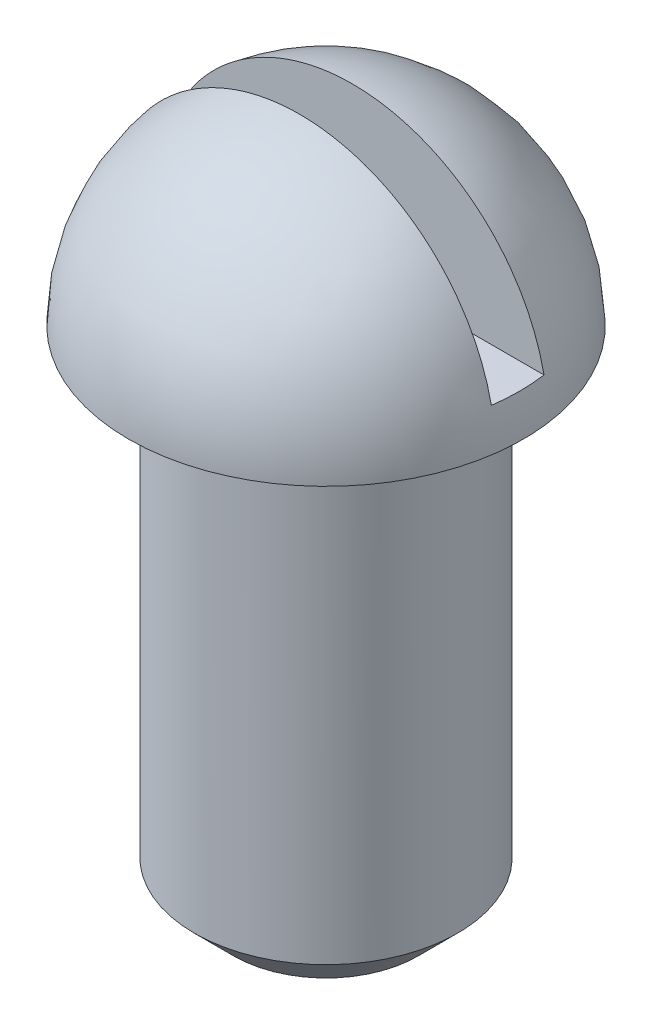
SolidWorks part; units mm, degrees
ref_plane "Front Plane" through (0, 0, 0) normal (0, 0, 1) x (1, 0, 0)
ref_plane "Top Plane" through (0, 0, 0) normal (0, 1, 0) x (1, 0, 0)
ref_plane "Right Plane" through (0, 0, 0) normal (1, 0, 0) x (0, 0, -1)
sketch "Sketch1" plane through (0, 0, 0) normal (1, 0, 0) x (0, 0, -1)
  line L0 (0, -38) -> (0, 15)
  line L1 (15, 0) -> (10, 0)
  line L3 (10, 0) -> (10, -38)
  line L4 (10, -38) -> (0, -38)
  arc A1 (15, 0) -> (0, 15) centre (0, 0) ccw
  point P1 (12.5, 0)
  point P6 (0, 0)
  point P9 (0, 0)
  dimension "D1" = 15
  dimension "D2" = 38
  dimension "D3" = 10
  dimension "D4" = 0
  dimension "D5" = 0
revolve "Revolve1" add sketch "Sketch1" angle 360 about L0
sketch "Sketch3" plane through (0, 0, 0) normal (1, 0, 0) x (0, 0, -1)
  line L0 (-10, 0) -> (10, 0) construction
  line L1 (-2, 18) -> (2, 18)
  line L2 (-2, 18) -> (-2, 3)
  line L3 (-2, 3) -> (2, 3)
  line L4 (2, 18) -> (2, 3)
  point P4 (0, 3)
  dimension "D1" = 15
  dimension "D2" = 4
  dimension "D3" = 3
extrude "Cut-Extrude1" cut sketch "Sketch3" against normal through all both and the other way through all
chamfer "Chamfer1" distance 3 angle 45 1 edges at (0, -38, -10)
